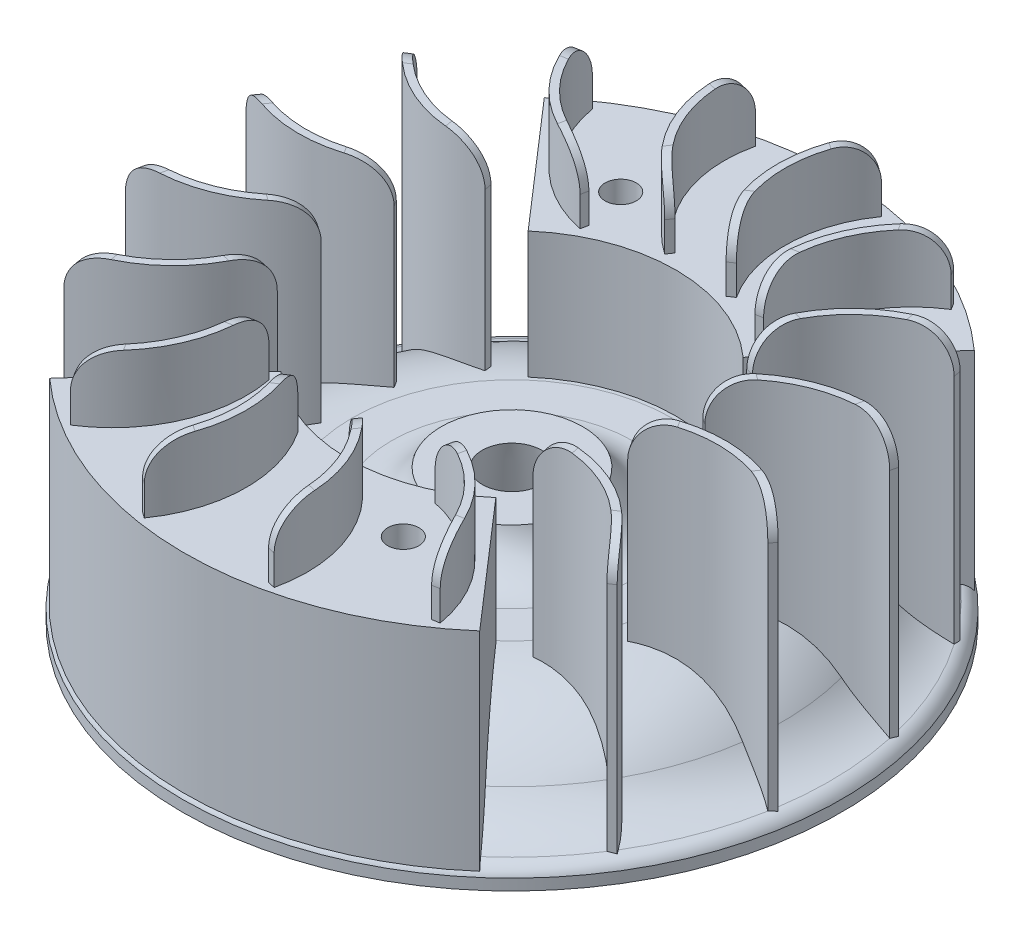
SolidWorks part; units mm, degrees
ref_plane "Front Plane" through (0, 0, 0) normal (0, 0, 1) x (1, 0, 0)
ref_plane "Top Plane" through (0, 0, 0) normal (0, 1, 0) x (1, 0, 0)
ref_plane "Right Plane" through (0, 0, 0) normal (1, 0, 0) x (0, 0, -1)
sketch "Sketch1" plane through (0, 0, 0) normal (0, 0, 1) x (1, 0, 0)
  line L0 (0, 0) -> (-25527.7334, 0) construction
  line L1 (0, 0) -> (0, 25527.7334) construction
  line L2 (4, 0) -> (9.5, 0)
  line L3 (16.2082, -5) -> (21.5, -5)
  line L4 (44.3, -16.5) -> (44.3, -18)
  line L5 (44.3, -18) -> (41.4816, -18)
  line L6 (4, 0) -> (6, -11)
  line L7 (6, -11) -> (25.3013, -11)
  arc A0 (9.5, 0) -> (16.2082, -5) centre (16.2082, 2) ccw
  arc A1 (21.5, -5) -> (36.2756, -11.5211) centre (21.5, -25) cw
  arc A2 (36.2756, -11.5211) -> (42.7119, -15.1854) centre (45.141, -3.4338) ccw
  arc A3 (42.7119, -15.1854) -> (44.3, -16.5) centre (42.2666, -17.3398) cw
  arc A4 (25.3013, -11) -> (39.8781, -17.3063) centre (25.3013, -31) cw
  arc A5 (41.4816, -18) -> (39.8781, -17.3063) centre (41.4816, -15.8) cw
  point P23 (40.5, -18)
  dimension "D1" = 7
  dimension "D3" = 2.2
  dimension "D5" = 20
  dimension "D7" = 12
  dimension "D15" = 2.2
  dimension "D16" = 20
  dimension "D2" = 5
  dimension "D4" = 1.5
  dimension "D6" = 13
  dimension "D8" = 21.5
  dimension "D9" = 44.3
  dimension "D10" = 40.5
  dimension "D11" = 4
  dimension "D12" = 9.5
  dimension "D13" = 6
  dimension "D14" = 11
revolve "Revolve2" add sketch "Sketch1" angle 360 about L1
ref_plane "Plane1" through (0, 21, 0) normal (0, 1, 0) x (1, 0, 0)
sketch "Sketch2" plane through (0, 21, 0) normal (0, 1, 0) x (1, 0, 0)
  line L0 (0, 0) -> (50000, 0) construction
  line L1 (0, 0) -> (0, 50000) construction
  line L2 (23.0893, 2.5619) -> (23.9165, 2)
  line L3 (41.9693, 10) -> (41.7476, 9.0249)
  circle A0 centre (0, 0) radius 43 construction
  circle A1 centre (0, 0) radius 24 construction
  arc A2 (23.9165, 2) -> (41.7476, 9.0249) centre (37.9791, -7.5522) cw
  circle A3 centre (0, 0) radius 42.7119 construction
  arc A4 (23.0893, 2.5619) -> (41.9693, 10) centre (37.9791, -7.5522) cw
  dimension "D1" = 48
  dimension "D2" = 86
  dimension "D3" = 17
  dimension "D5" = 2
  dimension "D6" = 10
  dimension "D4" = 1
extrude "Boss-Extrude1" add sketch "Sketch2" against normal up to next contours A2 L3 A4 L2
fillet "Fillet1" radius 5 2 edges at (41.8584, 21, -9.5124) (23.5029, 21, -2.2809)
pattern_circular "CirPattern1" count 16 over 360 about axis through (0, 0, 0) along (0, 1, 0) of "Boss-Extrude1", "Fillet1"
sketch "Sketch7" plane through (0, 21, 0) normal (0, 1, 0) x (1, 0, 0)
  line L0 (0, 0) -> (0, 50000) construction
  line L2 (-14.4333, 16.6036) -> (-28.8666, 33.2072)
  line L3 (14.7209, 16.3492) -> (29.4417, 32.6984)
  line L4 (-14.7209, -16.3492) -> (-29.4417, -32.6984)
  line L5 (14.4333, -16.6036) -> (28.8666, -33.2072)
  arc A0 (14.7209, 16.3492) -> (-14.4333, 16.6036) centre (0, 0) ccw
  arc A1 (-14.7209, -16.3492) -> (14.4333, -16.6036) centre (0, 0) ccw
  circle A2 centre (0, 0) radius 44
  arc A3 (-29.4417, -32.6984) -> (28.8666, -33.2072) centre (0, 0) ccw
  arc A4 (29.4417, 32.6984) -> (-28.8666, 33.2072) centre (0, 0) ccw
  dimension "D2" = 44
  dimension "D3" = 41
  dimension "D4" = 42
  dimension "D5" = 42
  dimension "D6" = 41
  dimension "D1" = 1
extrude "Boss-Extrude15" add sketch "Sketch7" against normal up to next from offset 9 offset against normal yes
sketch "Sketch8" plane through (0, 12, 0) normal (0, 1, 0) x (1, 0, 0)
  line L0 (0, 0) -> (-23.1965, 49.745) construction
  line L1 (-23.1965, 49.745) -> (0, 0) construction
  line L2 (0, 0) -> (17.5417, 50.9448) construction
  line L3 (0, 0) -> (22.4815, -48.2118) construction
  line L4 (0, 0) -> (-16.5661, -48.1114) construction
  line L5 (0, -200000) -> (0, 250000) construction
  dimension "D1" = 25
  dimension "D2" = 19
  dimension "D3" = 19
  dimension "D4" = 25
hole_wizard "M5 Tapped Hole3" positions "3DSketch2" profile "Sketch10" tap size "M5" standard "ISO"
sketch3d "3DSketch2"
  line L0 (0, 12, 0) -> (-23.1965, 12, -49.745) construction
  line L1 (0, 12, 0) -> (17.5417, 12, -50.9448) construction
  line L2 (0, 12, 0) -> (-16.5661, 12, 48.1114) construction
  line L3 (0, 12, 0) -> (22.4815, 12, 48.2118) construction
  point P0 (-12.7645, 12, -27.3736)
  point P4 (9.8333, 12, -28.5579)
  point P8 (-9.8333, 12, 28.5579)
  point P12 (12.7645, 12, 27.3736)
  dimension "D1" = 32.5
  dimension "D2" = 32.5
  dimension "D3" = 32.5
  dimension "D4" = 32.5
sketch "Sketch10" plane through (-12.7645, 12, -27.3736) normal (1, 0, 0) x (0, 0, 1)
  line L0 (0, 0) -> (0, 14.7618)
  line L1 (0, 14.7618) -> (2.1, 13.5)
  line L2 (2.1, 13.5) -> (2.1, 0)
  line L5 (2.1, 0) -> (0, 0)
  line L10 (0, 14.7618) -> (-2.1, 13.5) construction
  line L11 (0, -6.35) -> (0, 107.95) construction
  dimension "Tap Drill Dia." = 4.2
  dimension "Tap Drill Depth" = 13.5
  dimension "Drill Angle" = 118
cosmetic thread "Hole Thread9" parameters "D1"=10, "D2"=5
cosmetic thread "Hole Thread10" parameters "D1"=10, "D2"=5
cosmetic thread "Hole Thread11" parameters "D1"=10, "D2"=5
cosmetic thread "Hole Thread12" parameters "D1"=10, "D2"=5
